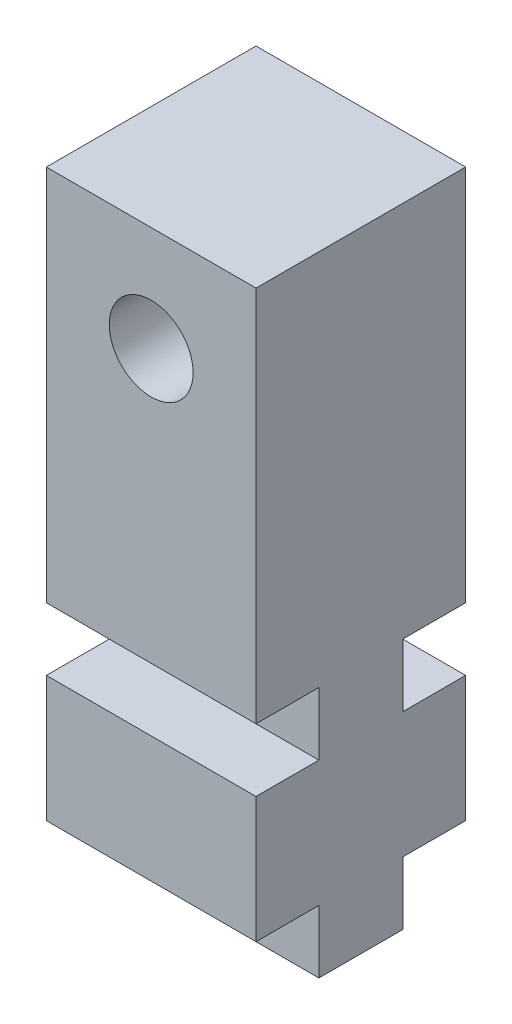
SolidWorks part; units mm, degrees
ref_plane "Front Plane" through (0, 0, 0) normal (0, 0, 1) x (1, 0, 0)
ref_plane "Top Plane" through (0, 0, 0) normal (0, 1, 0) x (1, 0, 0)
ref_plane "Right Plane" through (0, 0, 0) normal (1, 0, 0) x (0, 0, -1)
sketch "Sketch2" plane through (0, 0, 0) normal (0, 0, 1) x (1, 0, 0)
  line L1 (-2.5, 7.5) -> (2.5, 7.5)
  line L2 (-2.5, 7.5) -> (-2.5, -7.5)
  line L3 (-2.5, -7.5) -> (2.5, -7.5)
  line L4 (2.5, 7.5) -> (2.5, -7.5)
  line L5 (-2.5, 7.5) -> (2.5, -7.5) construction
  line L6 (-2.5, -7.5) -> (2.5, 7.5) construction
  circle A0 centre (0, 5) radius 1
  point P0 (0, 0)
  dimension "D3" = 2
  dimension "D1" = 5
  dimension "D2" = 15
  dimension "D4" = 12.5
extrude "Boss-Extrude1" add sketch "Sketch2" along normal mid plane 5
sketch "Sketch3" plane through (2.5, 0, 0) normal (1, 0, 0) x (0, 0, -1)
  line L0 (-2.5, -7.5) -> (-2.5, 7.5) construction
  line L1 (-2.5, -1.5) -> (-1, -1.5)
  line L2 (-2.5, -1.5) -> (-2.5, -3)
  line L3 (-2.5, -3) -> (-1, -3)
  line L4 (-1, -1.5) -> (-1, -3)
  line L6 (-2.5, -6) -> (-1, -6)
  line L7 (-2.5, -6) -> (-2.5, -7.5)
  line L8 (-2.5, -7.5) -> (-1, -7.5)
  line L9 (-1, -6) -> (-1, -7.5)
  line L10 (0, 11.5792) -> (0, -14.1326) construction
  line L11 (1, -6) -> (1, -7.5)
  line L12 (2.5, -7.5) -> (1, -7.5)
  line L13 (2.5, -6) -> (2.5, -7.5)
  line L14 (2.5, -6) -> (1, -6)
  line L15 (1, -1.5) -> (1, -3)
  line L16 (2.5, -3) -> (1, -3)
  line L17 (2.5, -1.5) -> (2.5, -3)
  line L18 (2.5, -1.5) -> (1, -1.5)
  line L19 (-2.5, -7.5) -> (2.5, -7.5) construction
  point P22 (-1.75, -6)
  dimension "D1" = 1.5
  dimension "D2" = 1.5
  dimension "D3" = 3
  dimension "D4" = 1.5
  dimension "D5" = 1.5
extrude "Cut-Extrude1" cut sketch "Sketch3" against normal through all
